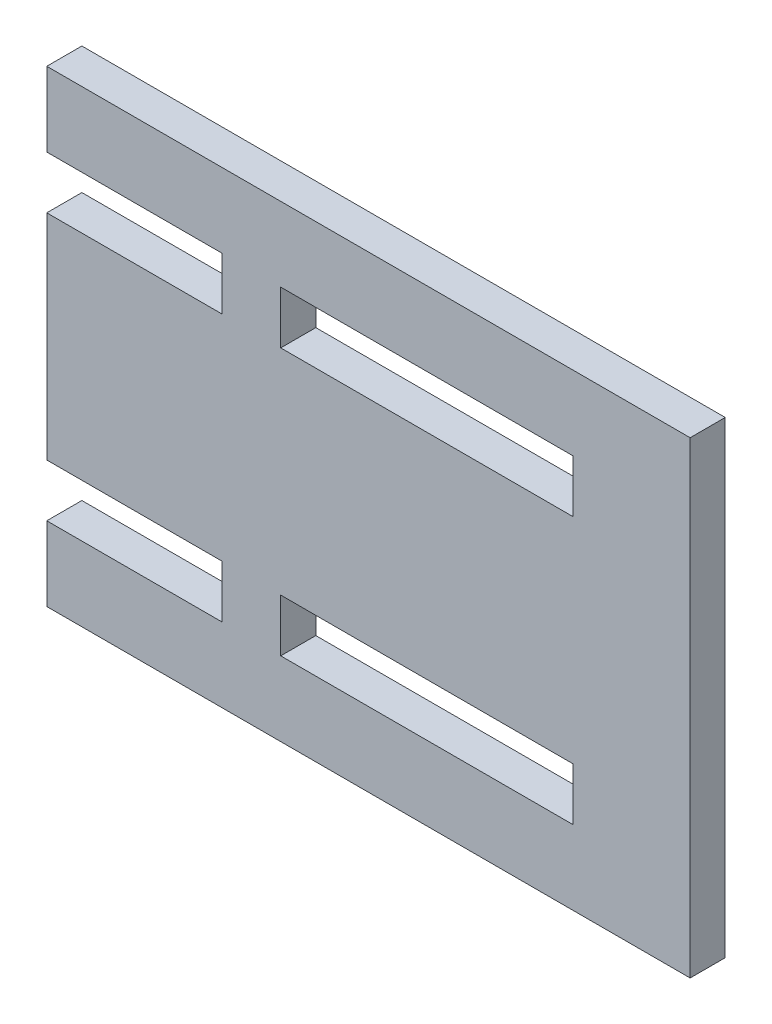
SolidWorks part; units mm, degrees
material "Acrylic (Medium-high impact)"
ref_plane "Front Plane" through (0, 0, 0) normal (0, 0, 1) x (1, 0, 0)
ref_plane "Top Plane" through (0, 0, 0) normal (0, 1, 0) x (1, 0, 0)
ref_plane "Right Plane" through (0, 0, 0) normal (1, 0, 0) x (0, 0, -1)
sketch "Sketch1" plane through (0, 0, 0) normal (0, 0, 1) x (1, 0, 0)
  line L1 (11.35, 0) -> (11.35, 18.3) construction
  line L2 (21.35, -10.85) -> (-33.65, -10.85)
  line L3 (21.35, -10.85) -> (21.35, 29.15)
  line L4 (21.35, 29.15) -> (-33.65, 29.15)
  line L5 (-33.65, -10.85) -> (-33.65, 29.15)
  line L6 (11.35, -4.5) -> (11.35, 0) construction
  line L7 (-113.1908, 22.8) -> (86.8092, 22.8) construction
  line L8 (-18.65, 18.3) -> (-64.9, 18.3) construction
  line L9 (-18.65, 22.8) -> (-18.65, 18.3) construction
  line L10 (-13.65, 22.8) -> (-13.65, 18.3) construction
  line L11 (11.35, 18.3) -> (11.35, 22.8) construction
  line L12 (11.35, 18.3) -> (-13.65, 18.3) construction
  line L13 (11.35, -4.5) -> (-13.65, -4.5) construction
  line L14 (11.35, 0) -> (-13.65, 0) construction
  line L15 (-13.65, 0) -> (-13.65, -4.5) construction
  line L16 (-18.65, 0) -> (-18.65, -4.5) construction
  line L17 (-18.65, -4.5) -> (-64.9, -4.5) construction
  line L18 (-18.65, 0) -> (-64.9, 0) construction
  line L19 (-33.65, 22.8) -> (-18.65, 22.8)
  line L20 (-18.65, 18.3) -> (-33.65, 18.3)
  line L21 (-18.65, 22.8) -> (-18.65, 18.3)
  line L22 (-13.65, 22.8) -> (-13.65, 18.3)
  line L23 (11.35, 18.3) -> (11.35, 22.8)
  line L24 (11.35, 18.3) -> (-13.65, 18.3)
  line L25 (11.35, -4.5) -> (11.35, 0)
  line L26 (11.35, -4.5) -> (-13.65, -4.5)
  line L27 (11.35, 0) -> (-13.65, 0)
  line L28 (-13.65, 0) -> (-13.65, -4.5)
  line L29 (-18.65, 0) -> (-18.65, -4.5)
  line L30 (-18.65, -4.5) -> (-33.65, -4.5)
  line L31 (-18.65, 0) -> (-33.65, 0)
  line L32 (-13.65, 22.8) -> (11.35, 22.8)
  point P8 (11.35, 9.15)
  point P9 (21.35, 9.15)
  dimension "D1" = 10
  dimension "D2" = 40
  dimension "D3" = 55
extrude "Boss-Extrude1" add sketch "Sketch1" against normal blind 3
